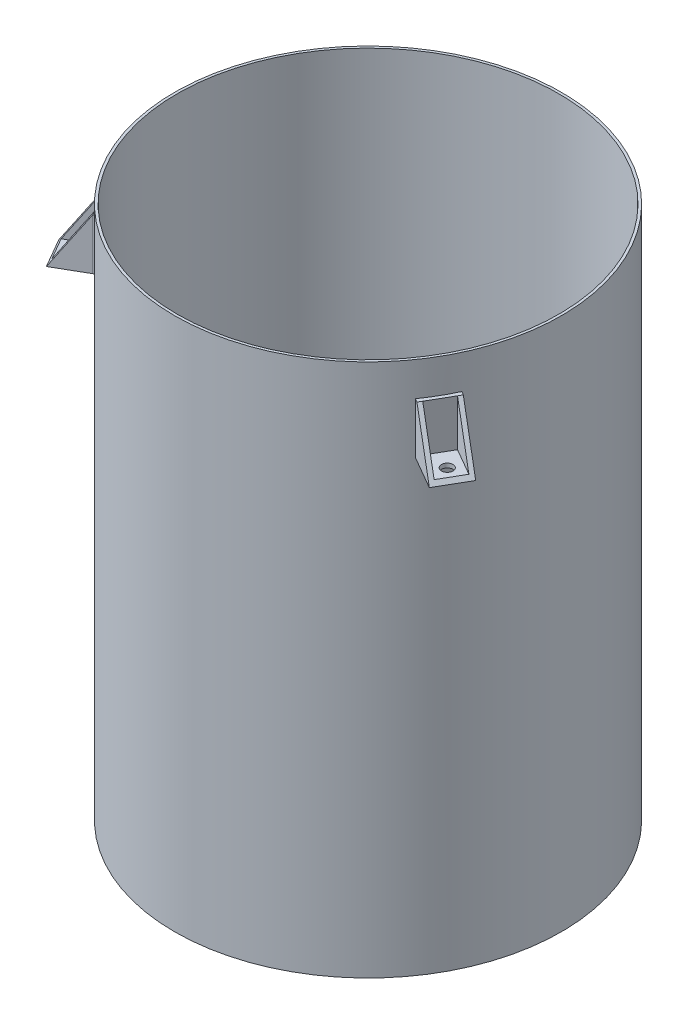
SolidWorks part; units mm, degrees
ref_plane "Front Plane" through (0, 0, 0) normal (0, 0, 1) x (1, 0, 0)
ref_plane "Top Plane" through (0, 0, 0) normal (0, 1, 0) x (1, 0, 0)
ref_plane "Right Plane" through (0, 0, 0) normal (1, 0, 0) x (0, 0, -1)
sketch "Sketch1" plane through (0, 0, 0) normal (0, 1, 0) x (1, 0, 0)
  circle A0 centre (0, 0) radius 225
  circle A1 centre (0, 0) radius 228
  dimension "D1" = 450
  dimension "D2" = 3
extrude "Boss-Extrude1" add sketch "Sketch1" along normal blind 628.8
sketch "Sketch3" plane through (0, 0, 0) normal (1, 0, 0) x (0, 0, -1)
  line L0 (218.8851, 0) -> (228, 0)
  line L1 (0, 0) -> (0, -50) construction
  line L2 (0, -46.9873) -> (0, -50)
  line L3 (-293.5293, 0) -> (-303, 0)
  line L4 (218.8851, 0) -> (0, -46.9873)
  line L5 (0, -50) -> (228, 0)
  dimension "D1" = 50
revolve "Revolve8" add sketch "Sketch3" angle 360 about L1
ref_plane "Plane1" through (0, 550, 0) normal (0, 1, 0) x (1, 0, 0)
ref_plane "Plane2" through (0, 0, 228) normal (0, 0, 1) x (1, 0, 0)
ref_plane "Plane3" through (0, -50, 0) normal (0, 1, 0) x (1, 0, 0)
sketch "Sketch5" plane through (0, -50, 0) normal (0, 1, 0) x (1, 0, 0)
  circle A0 centre (0, 0) radius 25
  circle A1 centre (0, 0) radius 28
  dimension "D1" = 50
  dimension "D2" = 3
extrude "Boss-Extrude2" add sketch "Sketch5" against normal blind 50 and the other way up to next
ref_plane "Plane4" through (0, 528.8, 0) normal (0, 1, 0) x (1, 0, 0)
sketch "Sketch6" plane through (0, 528.8, 0) normal (0, 1, 0) x (1, 0, 0)
  line L0 (0, 0) -> (0, 228) construction
  line L6 (0, 232.1324) -> (0, 262.7308) construction
  line L7 (0, 232.1211) -> (20, 232.1211)
  line L8 (0, 232.1211) -> (-20, 232.1211)
  line L9 (20, 232.1211) -> (20, 227.1211)
  line L10 (-20, 227.1211) -> (-20, 232.1211)
  line L11 (0, 232.1324) -> (0, 228) construction
  arc A1 (20, 227.1211) -> (-20, 227.1211) centre (0, 0) ccw
  circle A2 centre (0, 0) radius 228 construction
  dimension "D3" = 20
  dimension "D1" = 5
  dimension "D4" = 20
extrude "Boss-Extrude3" add sketch "Sketch6" along normal blind 60
sketch "Sketch7" plane through (0, 0, -232.1211) normal (0, 0, -1) x (-1, 0, 0)
  line L0 (-20, 588.8) -> (-20, 528.8)
  line L1 (270.2247, 528.8) -> (-270.2247, 528.8) construction
  line L2 (-20, 588.8) -> (-20, 528.8) construction
  line L3 (-20, 528.8) -> (19.9799, 528.8)
  line L4 (19.9799, 528.8) -> (20, 588.8)
  line L5 (20, 588.8) -> (15, 588.8)
  line L6 (-20, 588.8) -> (20, 588.8) construction
  line L7 (15, 588.8) -> (15, 533.8)
  line L8 (15, 533.8) -> (-15, 533.8)
  line L9 (-15, 533.8) -> (-15, 588.8)
  line L10 (20, 588.8) -> (-20, 588.8) construction
  line L11 (-15, 588.8) -> (-20, 588.8)
  dimension "D1" = 5
  dimension "D2" = 5
  dimension "D3" = 5
extrude "Boss-Extrude4" add sketch "Sketch7" along normal blind 40
sketch "Sketch8" plane through (-19.8031, -0.0066, 0) normal (-1, -0.0003, 0) x (0, 0, 1)
  line L0 (-232.1211, 588.8067) -> (-272.1211, 528.8067)
  line L2 (-272.1211, 528.8067) -> (-272.1211, 588.8067)
  line L3 (-272.1211, 588.8067) -> (-232.1211, 588.8067)
extrude "Cut-Extrude1" cut sketch "Sketch8" against normal blind 40
pattern_circular "CirPattern1" count 3 over 360 about axis through (0, 0, 0) along (0, 1, 0) of "Boss-Extrude3", "Cut-Extrude1", "Boss-Extrude4"
sketch "Sketch10" plane through (0, 533.8, 0) normal (0, 1, 0) x (1, 0, 0)
  line L0 (0, 0) -> (0, 312.7758) construction
  line L1 (0, 0) -> (287.8187, -166.1722) construction
  line L2 (0, 0) -> (-409.5298, -236.4421) construction
  circle A0 centre (0, 0) radius 255 construction
  circle A1 centre (0, 255) radius 6.75
  circle A2 centre (-220.8365, -127.5) radius 6.75
  circle A3 centre (220.8365, -127.5) radius 6.75
  dimension "D1" = 510
  dimension "D4" = 13.5
  dimension "D5" = 13.5
  dimension "D6" = 13.5
  dimension "D2" = 120
  dimension "D3" = 120
extrude "Cut-Extrude2" cut sketch "Sketch10" against normal blind 40
